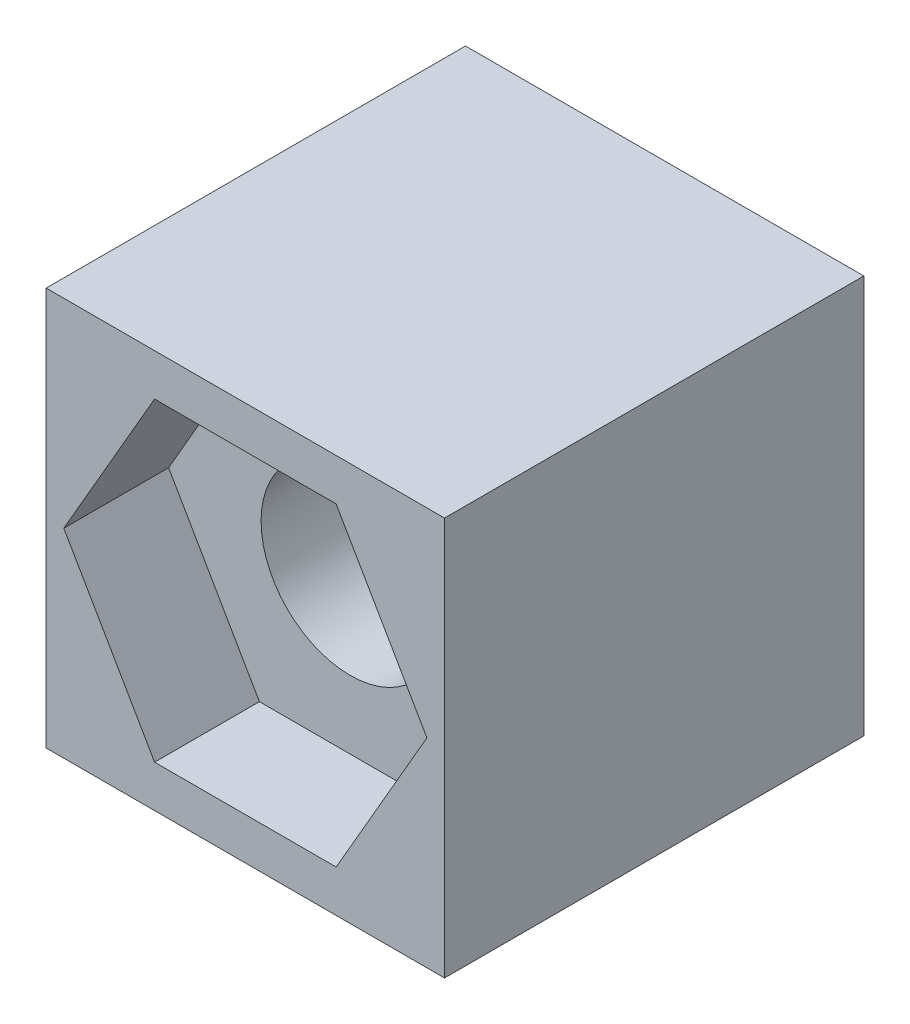
SolidWorks part; units mm, degrees
ref_plane "Front" through (0, 0, 0) normal (0, 0, 1) x (1, 0, 0)
ref_plane "Top" through (0, 0, 0) normal (0, 1, 0) x (1, 0, 0)
ref_plane "Right" through (0, 0, 0) normal (1, 0, 0) x (0, 0, -1)
sketch "Sketch1" plane through (0, 0, 0) normal (0, 0, 1) x (1, 0, 0)
  line L1 (0, 0) -> (7.6, 0)
  line L2 (0, 0) -> (0, 7.6)
  line L3 (0, 7.6) -> (7.6, 7.6)
  line L4 (7.6, 0) -> (7.6, 7.6)
  circle A0 centre (3.8, 3.8) radius 1.7
  point P8 (3.8, 7.6)
  point P9 (0, 3.8)
  dimension "D2" = 3.4
  dimension "D1" = 7.6
extrude "Boss-Extrude1" add sketch "Sketch1" along normal blind 8
sketch "Sketch3" plane through (0, 0, 8) normal (0, 0, 1) x (1, 0, 0)
  line L1 (5.5321, 0.8) -> (7.2641, 3.8)
  line L2 (7.2641, 3.8) -> (5.5321, 6.8)
  line L3 (5.5321, 6.8) -> (2.0679, 6.8)
  line L4 (2.0679, 6.8) -> (0.3359, 3.8)
  line L5 (0.3359, 3.8) -> (2.0679, 0.8)
  line L6 (2.0679, 0.8) -> (5.5321, 0.8)
  line L8 (7.6, 7.6) -> (0, 7.6) construction
  circle A0 centre (3.8, 3.8) radius 3 construction
  dimension "D1" = 6
extrude "Cut-Extrude1" cut sketch "Sketch3" against normal blind 2
